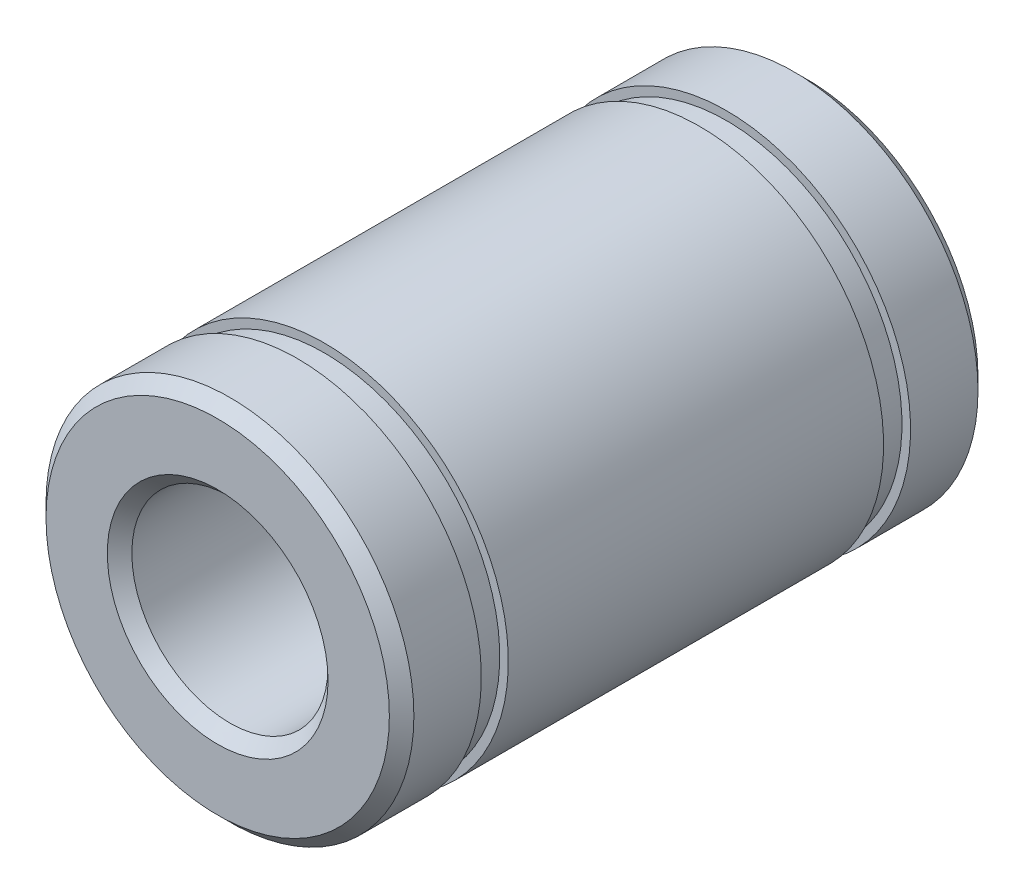
SolidWorks part; units mm, degrees
material "合金钢"
ref_plane "前视基准面" through (0, 0, 0) normal (0, 0, 1) x (1, 0, 0)
ref_plane "上视基准面" through (0, 0, 0) normal (0, 1, 0) x (1, 0, 0)
ref_plane "右视基准面" through (0, 0, 0) normal (1, 0, 0) x (0, 0, -1)
sketch "草图1" plane through (0, 0, 0) normal (0, 0, 1) x (1, 0, 0)
  circle A0 centre (0, 0) radius 4
  circle A1 centre (0, 0) radius 7.5
  dimension "D1" = 15
  dimension "D2" = 8
extrude "凸台-拉伸1" add sketch "草图1" along normal blind 24
chamfer "倒角1" distance 0.5 angle 45 4 edges at (4, 0, 24) (7.5, 0, 24) (4, 0, 0) (7.5, 0, 0)
sketch "草图2" plane through (0, 0, 0) normal (0, 1, 0) x (1, 0, 0)
  line L0 (0, 0) -> (0, -25.584) construction
  line L1 (10.1595, -12) -> (-11.4701, -12) construction
  line L2 (4.5, 0) -> (-4.5, 0) construction
  line L3 (-7, -24) -> (7, -24) construction
  line L4 (7.5, -23.5) -> (7.5, -0.5) construction
  line L5 (7.5, -3.25) -> (7.15, -3.25)
  line L6 (7.5, -3.25) -> (7.5, -4.35)
  line L7 (7.5, -4.35) -> (7.15, -4.35)
  line L8 (7.15, -3.25) -> (7.15, -4.35)
  line L9 (7.15, -20.75) -> (7.15, -19.65)
  line L10 (7.5, -19.65) -> (7.15, -19.65)
  line L11 (7.5, -20.75) -> (7.5, -19.65)
  line L12 (7.5, -20.75) -> (7.15, -20.75)
  dimension "D1" = 14.3
  dimension "D2" = 1.1
  dimension "D3" = 17.5
revolve "切除-旋转1" cut sketch "草图2" angle 360 about L0
